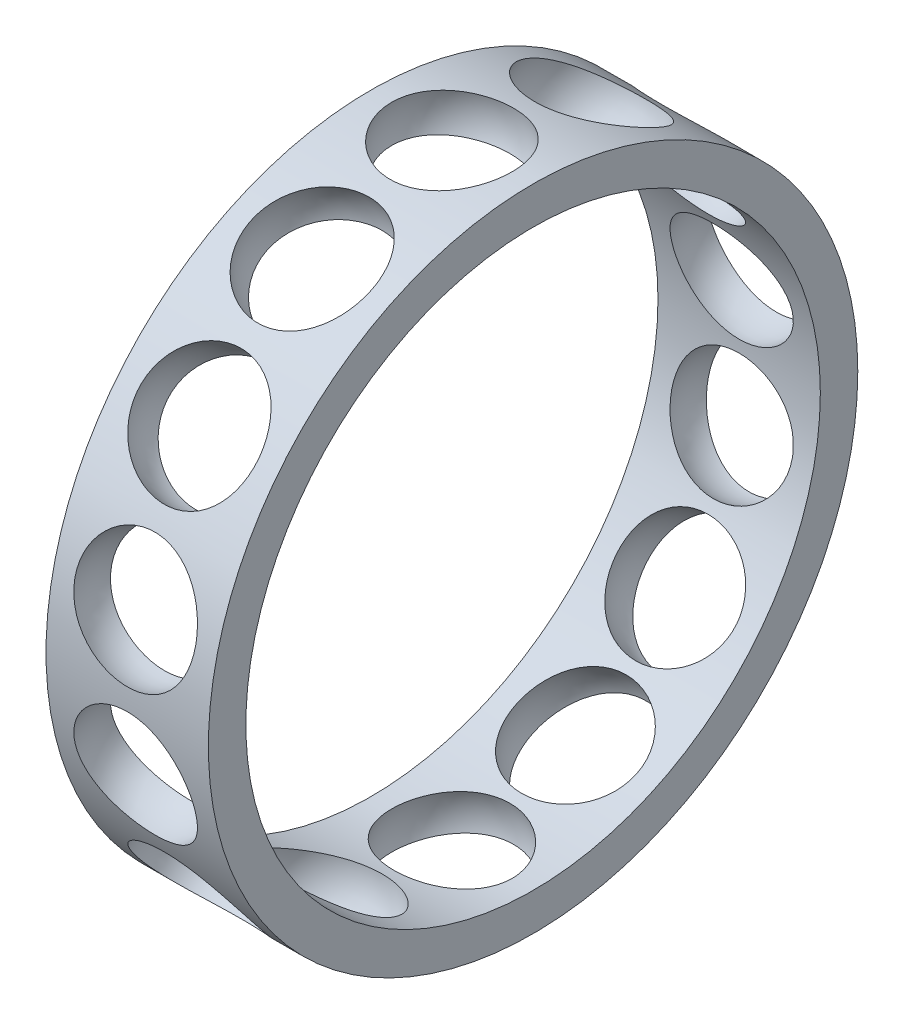
SolidWorks part; units mm, degrees
ref_plane "Plan1" through (0, 0, 0) normal (0, 0, 1) x (1, 0, 0)
ref_plane "Plan2" through (0, 0, 0) normal (0, 1, 0) x (1, 0, 0)
ref_plane "Plan3" through (0, 0, 0) normal (1, 0, 0) x (0, 0, -1)
sketch "Esquisse1" plane through (0, 0, 0) normal (0, 0, 1) x (1, 0, 0)
  line L0 (5.2916, 23) -> (18.2916, 23)
  line L1 (5.2916, 23) -> (5.2916, 26)
  line L2 (5.2916, 26) -> (18.2916, 26)
  line L3 (18.2916, 26) -> (18.2916, 23)
  line L5 (25, 0) -> (-5, 0) construction
  line L6 (43.7916, 0) -> (-206.2084, 0) construction
revolve "Base-Révolution" add sketch "Esquisse1" angle 360 about L5
sketch "Esquisse2" plane through (0, 0, 0) normal (0, 0, 1) x (1, 0, 0)
  line L0 (11.7916, 31.5544) -> (11.7916, 16.3043) construction
  line L1 (43.7916, 0) -> (-206.2084, 0) construction
  line L3 (11.7916, 32.288) -> (11.7916, 17.4195) construction
  line L4 (11.7916, 29.55) -> (11.7916, 19.45)
  arc A0 (11.7916, 19.45) -> (11.7916, 29.55) centre (11.7916, 24.5) ccw
  dimension "D1" = 24.5
revolve "Enlèvement de matière-Révolution1" cut sketch "Esquisse2" angle 360 about L3
pattern_circular "Répétition circulaire1" count 14 every 25.714
